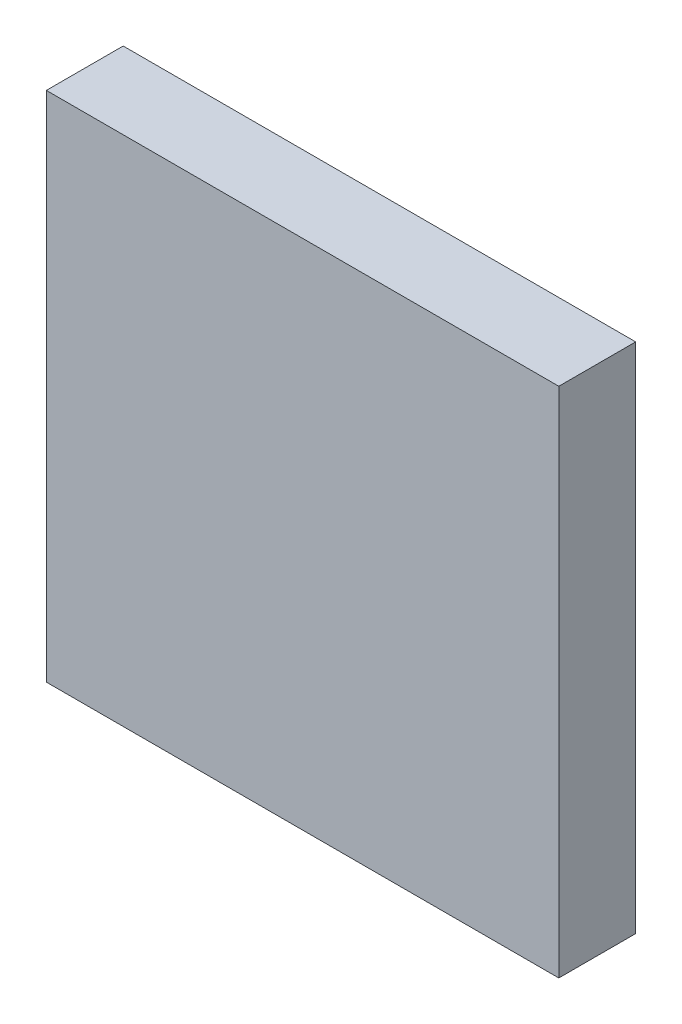
SolidWorks part; units mm, degrees
ref_plane "前视基准面" through (0, 0, 0) normal (0, 0, 1) x (1, 0, 0)
ref_plane "上视基准面" through (0, 0, 0) normal (0, 1, 0) x (1, 0, 0)
ref_plane "右视基准面" through (0, 0, 0) normal (1, 0, 0) x (0, 0, -1)
other "Configuration Table"
sketch "草图1" plane through (0, 0, 0) normal (0, 0, 1) x (1, 0, 0)
  line L1 (-500, -125) -> (500, -125)
  line L2 (-500, -125) -> (-500, 125)
  line L3 (-500, 125) -> (500, 125)
  line L4 (500, -125) -> (500, 125)
  line L5 (-500, -125) -> (500, 125) construction
  line L6 (-500, 125) -> (500, -125) construction
  point P0 (0, 0)
extrude "凸台-拉伸1" add sketch "草图1" along normal blind 150
sketch "草图2" plane through (0, 0, 0) normal (0, 0, 1) x (1, 0, 0)
  line L1 (-500, 125) -> (500, 125)
  line L2 (-500, 125) -> (-500, 375)
  line L3 (-500, 375) -> (500, 375)
  line L4 (500, 125) -> (500, 375)
  line L5 (-500, 125) -> (500, 375) construction
  line L6 (-500, 375) -> (500, 125) construction
  point P0 (0, 250)
extrude "凸台-拉伸2" add sketch "草图2" along normal blind 150
sketch "草图3" plane through (0, 0, 0) normal (0, 0, 1) x (1, 0, 0)
  line L1 (-500, 375) -> (500, 375)
  line L2 (-500, 375) -> (-500, 625)
  line L3 (-500, 625) -> (500, 625)
  line L4 (500, 375) -> (500, 625)
  line L5 (-500, 375) -> (500, 625) construction
  line L6 (-500, 625) -> (500, 375) construction
  point P0 (0, 500)
extrude "凸台-拉伸3" add sketch "草图3" along normal blind 150
sketch "草图4" plane through (0, 0, 0) normal (0, 0, 1) x (1, 0, 0)
  line L1 (-500, 625) -> (500, 625)
  line L2 (-500, 625) -> (-500, 875)
  line L3 (-500, 875) -> (500, 875)
  line L4 (500, 625) -> (500, 875)
  line L5 (-500, 625) -> (500, 875) construction
  line L6 (-500, 875) -> (500, 625) construction
  point P0 (0, 750)
extrude "凸台-拉伸4" add sketch "草图4" along normal blind 150
